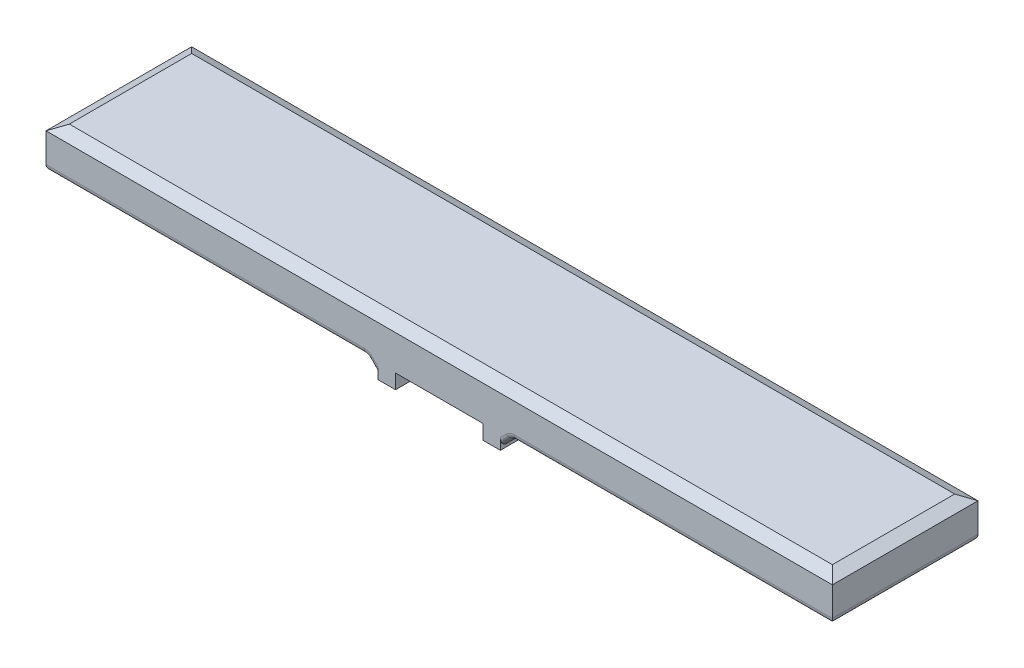
SolidWorks part; units mm, degrees
material "C355.0-T61 Permanent Mold cast (SS)"
ref_plane "Front Plane" through (0, 0, 0) normal (0, 0, 1) x (1, 0, 0)
ref_plane "Top Plane" through (0, 0, 0) normal (0, 1, 0) x (1, 0, 0)
ref_plane "Right Plane" through (0, 0, 0) normal (1, 0, 0) x (0, 0, -1)
sketch "Sketch1" plane through (0, 0, 0) normal (0, 1, 0) x (1, 0, 0)
  line L1 (-675, 125) -> (675, 125)
  line L2 (-675, 125) -> (-675, -125)
  line L3 (-675, -125) -> (675, -125)
  line L4 (675, 125) -> (675, -125)
  line L5 (-675, 125) -> (675, -125) construction
  line L6 (-675, -125) -> (675, 125) construction
  point P0 (0, 0)
  dimension "D1" = 1350
  dimension "D2" = 250
extrude "Boss-Extrude1" add sketch "Sketch1" along normal blind 70 contours L1 L4 L3 L2
chamfer "Chamfer1" distance 10 distance2 20 4 edges at (0, 70, -125) (675, 70, 0) (0, 70, 125) (-675, 70, 0)
shell "Shell1" thickness 10
sketch "Sketch2" plane through (0, 0, 0) normal (0, -1, 0) x (1, 0, 0)
  line L0 (-75, 125) -> (-75, -125)
  line L1 (-675, 125) -> (675, 125) construction
  line L2 (-675, -125) -> (675, -125) construction
  line L3 (-105, 125) -> (-105, -125)
  line L4 (-105, 125) -> (-75, 125)
  line L5 (-105, -125) -> (-75, -125)
  line L6 (0, 320.5208) -> (0, -388.3091) construction
  line L7 (105, -125) -> (75, -125)
  line L8 (105, 125) -> (75, 125)
  line L9 (105, 125) -> (105, -125)
  line L10 (75, 125) -> (75, -125)
  dimension "D1" = 75
  dimension "D2" = 30
extrude "Boss-Extrude2" add sketch "Sketch2" along normal blind 25
chamfer "Chamfer2" distance 20 angle 45 2 edges at (-105, 0, 0) (105, 0, 0)
fillet "Fillet1" radius 10 12 edges at (115, -10, -125) (115, -10, 125) (-115, -10, 125) (-115, -10, -125) (675, 0, 0) (400, 0, -125) (125, 0, 0) (400, 0, 125) (-675, 0, 0) (-400, 0, 125) (-125, 0, 0) (-400, 0, -125)
sketch "Sketch3" plane through (0, 0, 0) normal (0, -1, 0) x (1, 0, 0)
  circle A0 centre (0, 0) radius 10
  dimension "D1" = 20
extrude "Boss-Extrude3" add sketch "Sketch3" along normal blind 25
chamfer "Chamfer3" distance 3 angle 45 1 edges at (0, -25, -10)
